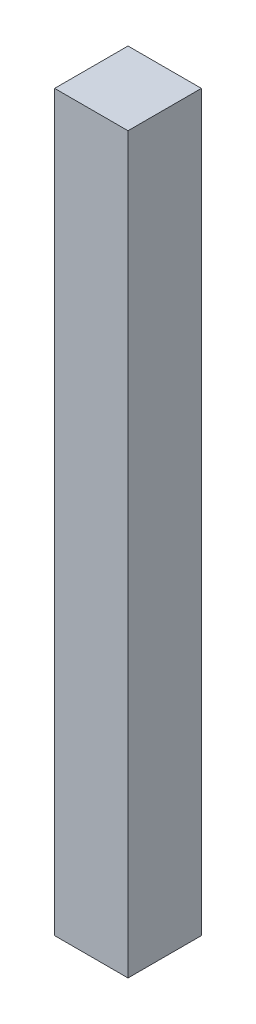
SolidWorks part; units mm, degrees
ref_plane "Front Plane" through (0, 0, 0) normal (0, 0, 1) x (1, 0, 0)
ref_plane "Top Plane" through (0, 0, 0) normal (0, 1, 0) x (1, 0, 0)
ref_plane "Right Plane" through (0, 0, 0) normal (1, 0, 0) x (0, 0, -1)
sketch "Sketch4" plane through (0, 0, 0) normal (0, 1, 0) x (1, 0, 0)
  line L0 (0, 0) -> (20, 0)
  line L1 (20, 0) -> (20, -20)
  line L2 (20, -20) -> (0, -20)
  line L3 (0, -20) -> (0, 0)
  dimension "D1" = 20
  dimension "D2" = 20
extrude "Boss-Extrude2" add sketch "Sketch4" along normal blind 200
